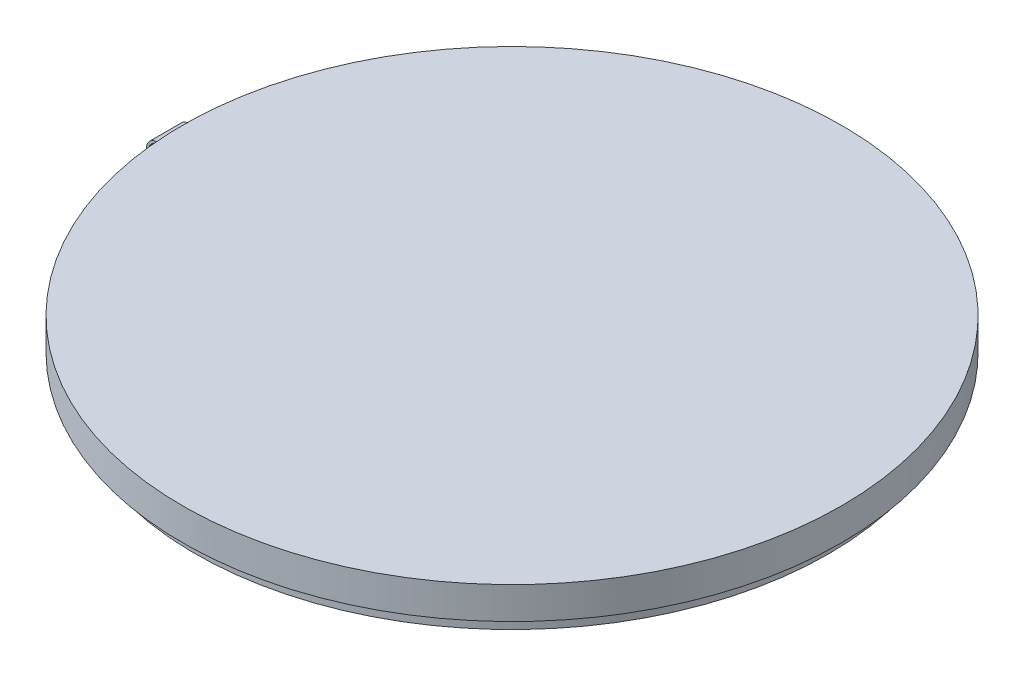
SolidWorks part; units mm, degrees
material "1023 Carbon Steel Sheet (SS)"
ref_plane "Front Plane" through (0, 0, 0) normal (0, 0, 1) x (1, 0, 0)
ref_plane "Top Plane" through (0, 0, 0) normal (0, 1, 0) x (1, 0, 0)
ref_plane "Right Plane" through (0, 0, 0) normal (1, 0, 0) x (0, 0, -1)
sketch "Sketch2" plane through (0, 0, 0) normal (0, 0, 1) x (1, 0, 0)
  line L0 (0, 0) -> (0, 2.54)
  line L1 (0, 2.54) -> (26.162, 2.54)
  line L2 (26.162, 2.54) -> (26.162, 0)
  line L3 (26.162, 0) -> (25.146, 0)
  line L4 (25.146, 0) -> (25.146, -1.27)
  line L5 (25.146, -1.27) -> (24.13, -1.27)
  line L6 (24.13, -1.27) -> (24.13, 0)
  line L7 (24.13, 0) -> (0, 0)
  line L8 (0, -1000) -> (0, 49000) construction
  dimension "D1" = 1.016
  dimension "D2" = 1.016
  dimension "D3" = 2.54
  dimension "D4" = 24.13
  dimension "D5" = 1.27
revolve "Revolve1" add sketch "Sketch2" angle 360 about L8
sketch "Sketch3" plane through (0, 0, 0) normal (0, 0, 1) x (1, 0, 0)
  line L0 (-25.4, 1.651) -> (-25.4, 0)
  line L1 (26.162, 2.54) -> (-26.162, 2.54) construction
  line L2 (-26.162, 0) -> (26.162, 0) construction
  line L3 (-25.4, 0) -> (-26.924, 0)
  line L4 (-26.924, 1.651) -> (-25.4, 1.651)
  line L5 (0, 0) -> (0, 2.54) construction
  arc A0 (-26.924, 0) -> (-26.924, 1.651) centre (-26.924, 0.8255) cw
  circle A1 centre (-26.924, 0.8255) radius 0.635
  point P12 (-25.5711, 2.54)
  point P13 (-25.4633, 1.7922)
  dimension "D3" = 1.27
  dimension "D1" = 25.4
  dimension "D2" = 1.524
  dimension "D4" = 1.651
extrude "Boss-Extrude1" add sketch "Sketch3" along normal mid plane 2.54
